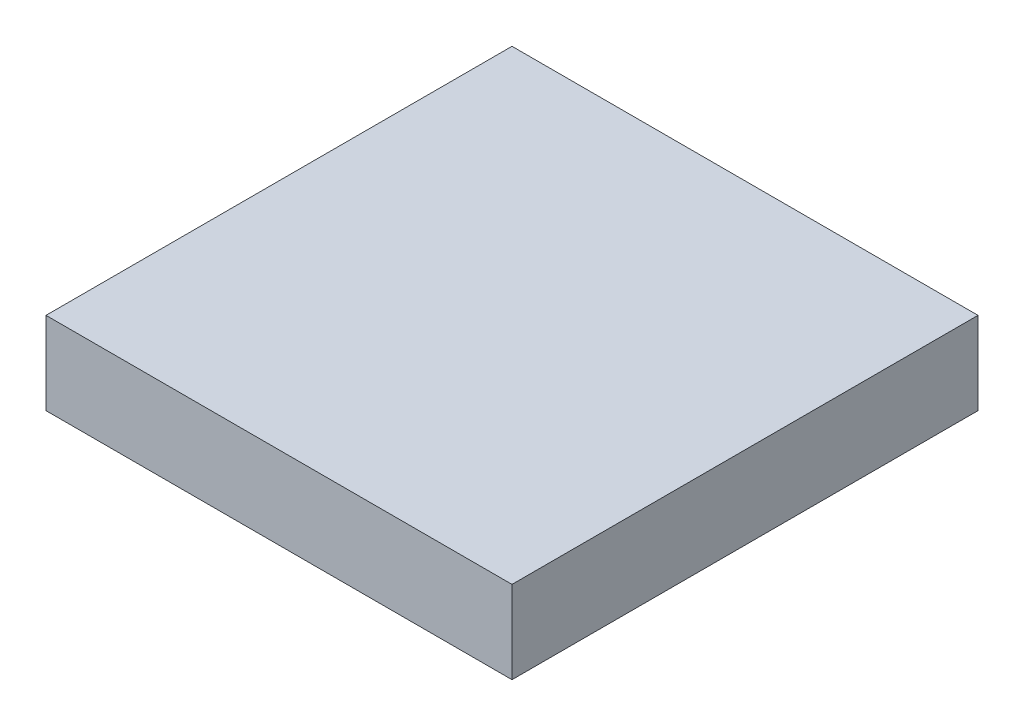
SolidWorks part; units mm, degrees
ref_plane "Front Plane" through (0, 0, 0) normal (0, 0, 1) x (1, 0, 0)
ref_plane "Top Plane" through (0, 0, 0) normal (0, 1, 0) x (1, 0, 0)
ref_plane "Right Plane" through (0, 0, 0) normal (1, 0, 0) x (0, 0, -1)
sketch "Sketch1" plane through (0, 0, 0) normal (0, 1, 0) x (1, 0, 0)
  line L1 (12.7, -12.7) -> (-12.7, -12.7)
  line L2 (12.7, -12.7) -> (12.7, 12.7)
  line L3 (12.7, 12.7) -> (-12.7, 12.7)
  line L4 (-12.7, -12.7) -> (-12.7, 12.7)
  line L5 (12.7, -12.7) -> (-12.7, 12.7) construction
  line L6 (12.7, 12.7) -> (-12.7, -12.7) construction
  point P0 (0, 0)
  dimension "D1" = 25.4
  dimension "D2" = 25.4
extrude "Boss-Extrude1" add sketch "Sketch1" along normal blind 4.5
